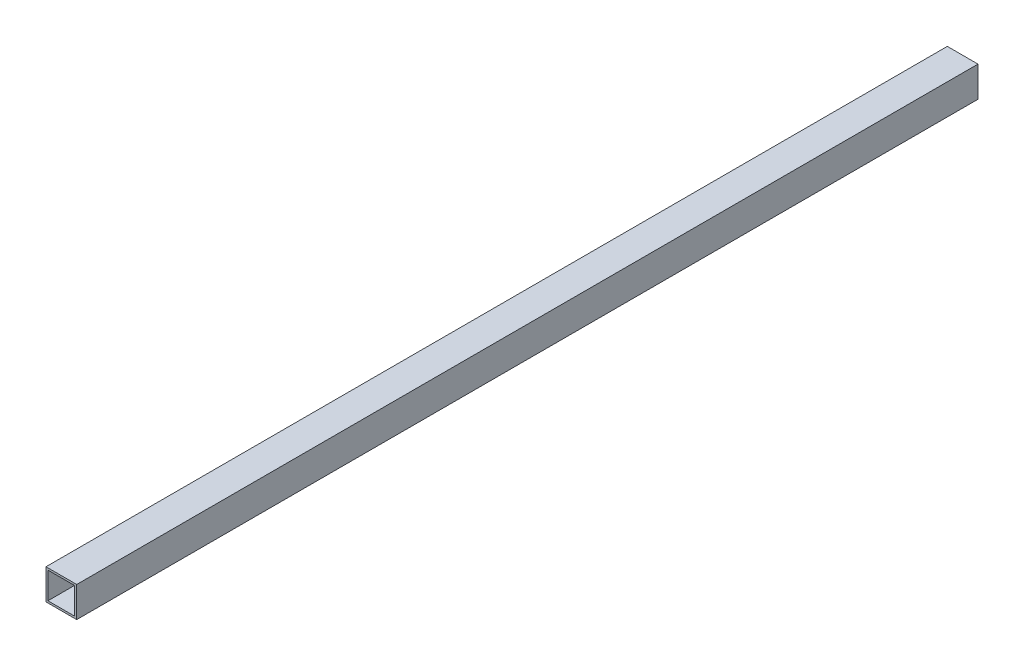
SolidWorks part; units mm, degrees
ref_plane "Alzado" through (0, 0, 0) normal (0, 0, 1) x (1, 0, 0)
ref_plane "Planta" through (0, 0, 0) normal (0, 1, 0) x (1, 0, 0)
ref_plane "Vista lateral" through (0, 0, 0) normal (1, 0, 0) x (0, 0, -1)
sketch "Croquis1" plane through (0, 0, 0) normal (0, 0, 1) x (1, 0, 0)
  line L1 (-69.6345, 22.2691) -> (-6.6345, 22.2691)
  line L2 (-69.6345, 22.2691) -> (-69.6345, -40.2309)
  line L3 (-69.6345, -40.2309) -> (-6.6345, -40.2309)
  line L4 (-6.6345, 22.2691) -> (-6.6345, -40.2309)
  line L5 (-65.6345, 18.2691) -> (-10.6345, 18.2691)
  line L6 (-65.6345, 18.2691) -> (-65.6345, -36.2309)
  line L7 (-65.6345, -36.2309) -> (-10.6345, -36.2309)
  line L8 (-10.6345, 18.2691) -> (-10.6345, -36.2309)
  dimension "D1" = 62.5
  dimension "D2" = 63
  dimension "D3" = 4
  dimension "D4" = 4
  dimension "D5" = 4
  dimension "D6" = 4
extrude "Saliente-Extruir1" add sketch "Croquis1" along normal blind 1850
